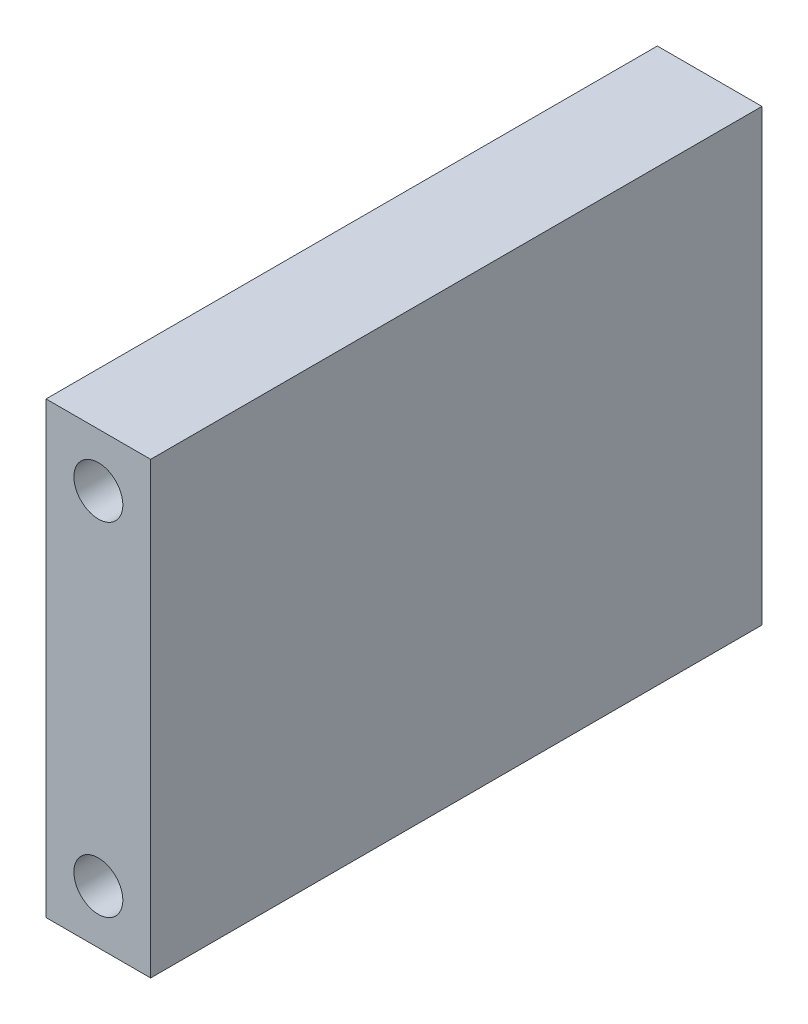
SolidWorks part; units mm, degrees
ref_plane "Ön Düzlem" through (0, 0, 0) normal (0, 0, 1) x (1, 0, 0)
ref_plane "Üst Düzlem" through (0, 0, 0) normal (0, 1, 0) x (1, 0, 0)
ref_plane "Sağ Düzlem" through (0, 0, 0) normal (1, 0, 0) x (0, 0, -1)
sketch "Çizim1" plane through (0, 0, 0) normal (0, 0, 1) x (1, 0, 0)
  line L0 (8.2196, -36.2523) -> (8.2196, 37.2315)
  line L1 (8.2196, 37.2315) -> (-8.8913, 37.2315)
  line L2 (-8.8913, 37.2315) -> (-8.8913, -36.2523)
  line L3 (-8.8913, -36.2523) -> (8.2196, -36.2523)
  circle A0 centre (-0.3359, -27.5104) radius 4
  circle A1 centre (-0.3359, 28.4896) radius 4
extrude "Yükseklik-Ekstrüzyon1" add sketch "Çizim1" along normal blind 100
